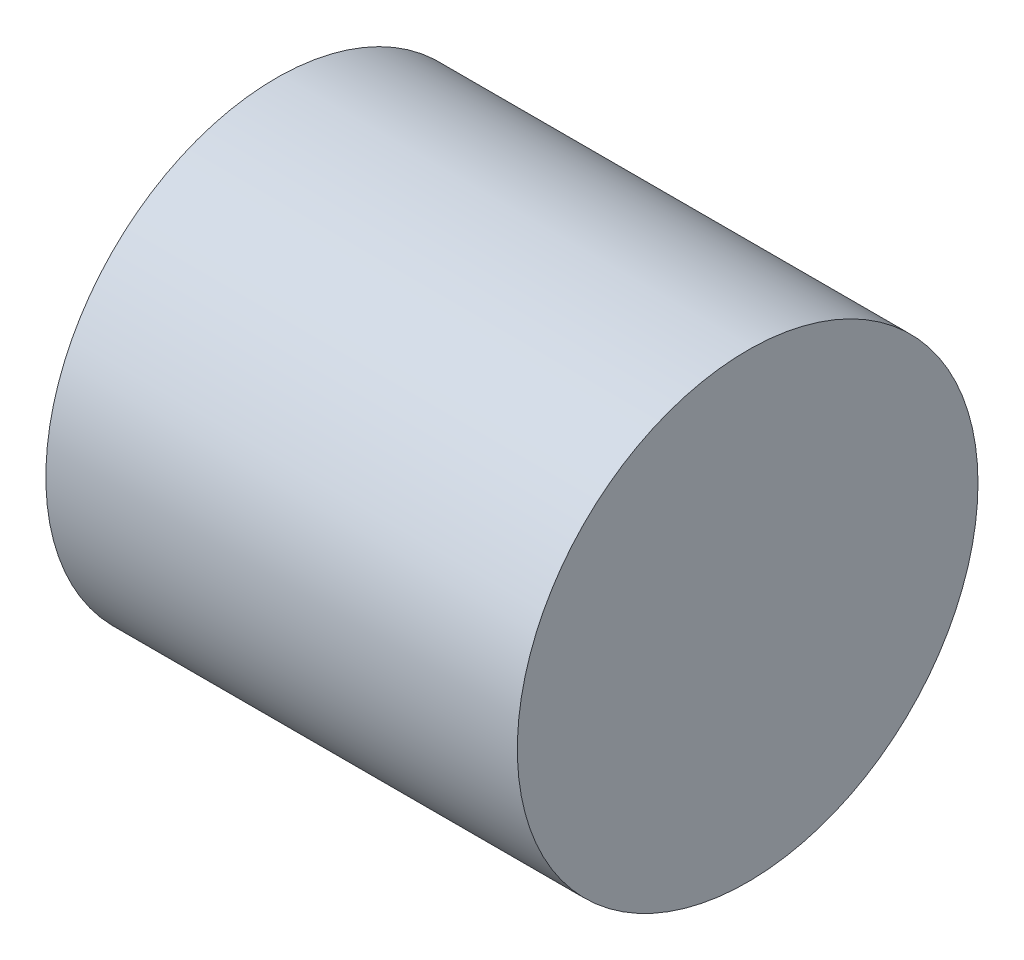
SolidWorks part; units mm, degrees
ref_plane "Front Plane" through (0, 0, 0) normal (0, 0, 1) x (1, 0, 0)
ref_plane "Top Plane" through (0, 0, 0) normal (0, 1, 0) x (1, 0, 0)
ref_plane "Right Plane" through (0, 0, 0) normal (1, 0, 0) x (0, 0, -1)
sketch "CurveSketch" plane through (0, 0, 0) normal (1, 0, 0) x (0, 0, -1)
  circle A0 centre (17.391, -9.173) radius 5.731
  dimension "D1" = 11.462
extrude "CurveBoss" add sketch "CurveSketch" along normal blind 11.731
